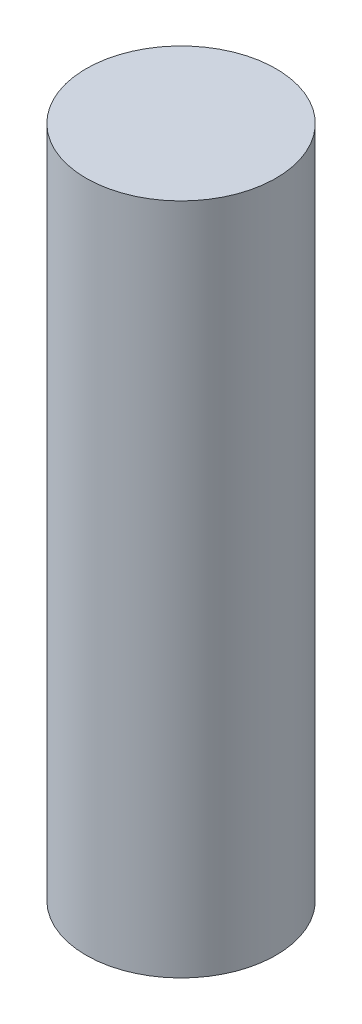
SolidWorks part; units mm, degrees
ref_plane "前视基准面" through (0, 0, 0) normal (0, 0, 1) x (1, 0, 0)
ref_plane "上视基准面" through (0, 0, 0) normal (0, 1, 0) x (1, 0, 0)
ref_plane "右视基准面" through (0, 0, 0) normal (1, 0, 0) x (0, 0, -1)
sketch "草图1" plane through (0, 0, 0) normal (0, 1, 0) x (1, 0, 0)
  circle A0 centre (0, 0) radius 4.5
  point P3 (-225.569, -24.8578)
extrude "凸台-拉伸1" add sketch "草图1" along normal blind 31.9
